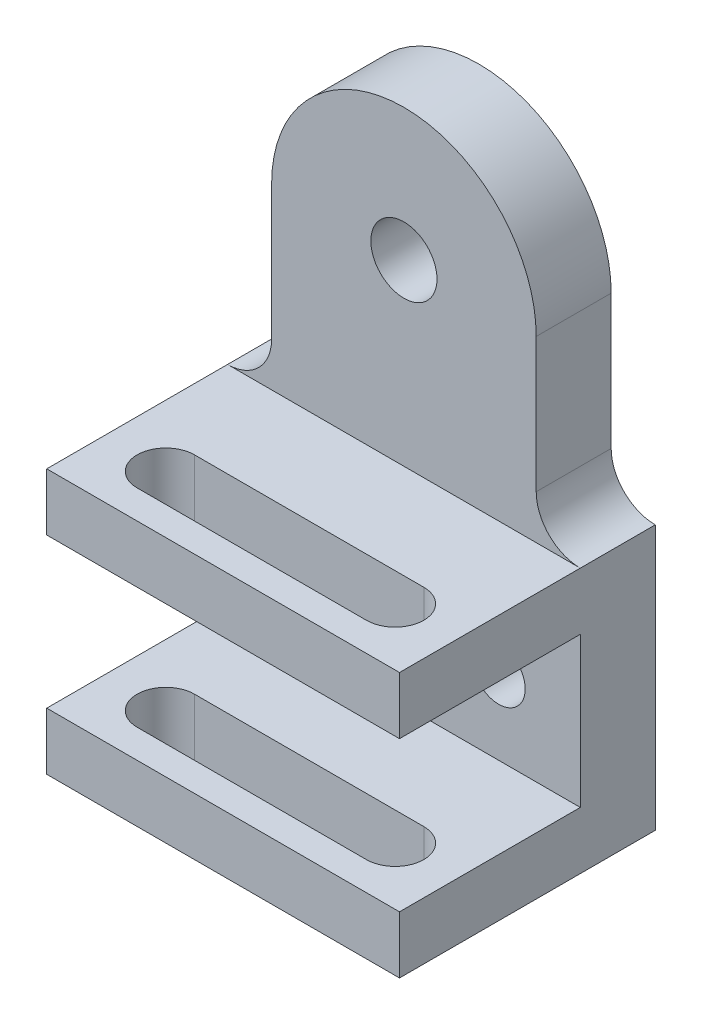
SolidWorks part; units mm, degrees
ref_plane "Front Plane" through (0, 0, 0) normal (0, 0, 1) x (1, 0, 0)
ref_plane "Top Plane" through (0, 0, 0) normal (0, 1, 0) x (1, 0, 0)
ref_plane "Right Plane" through (0, 0, 0) normal (1, 0, 0) x (0, 0, -1)
sketch "Sketch1" plane through (0, 0, 0) normal (0, 0, 1) x (1, 0, 0)
  line L0 (0, 0) -> (2032, 0)
  line L1 (2032, 0) -> (2032, 1524)
  line L3 (0, 1524) -> (0, 0)
  line L4 (1016, 0) -> (1016, 2552.7) construction
  line L5 (0, 762) -> (2032, 762) construction
  line L6 (1778, 2552.7) -> (1778, 1778)
  line L7 (254, 2552.7) -> (254, 1778)
  arc A2 (1778, 2552.7) -> (254, 2552.7) centre (1016, 2552.7) ccw
  arc A3 (0, 1524) -> (254, 1778) centre (0, 1778) ccw
  arc A4 (1778, 1778) -> (2032, 1524) centre (2032, 1778) ccw
  dimension "D4" = 1524
  dimension "D5" = 254
  dimension "D6" = 254
  dimension "D1" = 2032
  dimension "D2" = 2552.7
  dimension "D3" = 1524
extrude "Boss-Extrude1" add sketch "Sketch1" along normal blind 431.8
sketch "Sketch2" plane through (0, 0, 431.8) normal (0, 0, 1) x (1, 0, 0)
  line L0 (1016, 0) -> (1016, 2552.7) construction
  line L2 (0, 762) -> (2032, 762) construction
  line L3 (0, 1524) -> (0, 0) construction
  line L4 (2032, 0) -> (2032, 1524) construction
  line L5 (0, 0) -> (2032, 0) construction
  circle A1 centre (469.9, 762) radius 152.4
  circle A2 centre (1562.1, 762) radius 152.4
  circle A3 centre (1016, 2552.7) radius 190.5
  dimension "D1" = 304.8
  dimension "D2" = 304.8
extrude "Cut-Extrude1" cut sketch "Sketch2" against normal blind 431.8
sketch "Sketch3" plane through (0, 0, 431.8) normal (0, 0, 1) x (1, 0, 0)
  line L0 (0, 0) -> (2032, 0)
  line L1 (2032, 0) -> (2032, 330.2)
  line L2 (2032, 0) -> (2032, 1524) construction
  line L3 (2032, 330.2) -> (0, 330.2)
  line L4 (0, 1524) -> (0, 0) construction
  line L5 (0, 330.2) -> (0, 0)
  line L6 (0, 1524) -> (2032, 1524)
  line L7 (2032, 1524) -> (2032, 1193.8)
  line L8 (2032, 1193.8) -> (0, 1193.8)
  line L9 (0, 1193.8) -> (0, 1524)
  line L10 (0, 0) -> (2032, 0) construction
  dimension "D1" = 2032
  dimension "D2" = 330.2
extrude "Boss-Extrude2" add sketch "Sketch3" along normal blind 1041.4
sketch "Sketch4" plane through (0, 1524, 0) normal (0, 1, 0) x (1, 0, 0)
  line L2 (0, -1473.2) -> (0, -431.8) construction
  line L3 (2032, -431.8) -> (0, -431.8) construction
  line L4 (355.6, -977.9) -> (1676.4, -977.9)
  line L5 (355.6, -1308.1) -> (1676.4, -1308.1)
  arc A0 (355.6, -977.9) -> (355.6, -1308.1) centre (355.6, -1143) ccw
  arc A1 (1676.4, -1308.1) -> (1676.4, -977.9) centre (1676.4, -1143) ccw
  dimension "D1" = 165.1
  dimension "D2" = 355.6
  dimension "D3" = 1676.4
  dimension "D4" = 711.2
extrude "Cut-Extrude2" cut sketch "Sketch4" against normal through all
